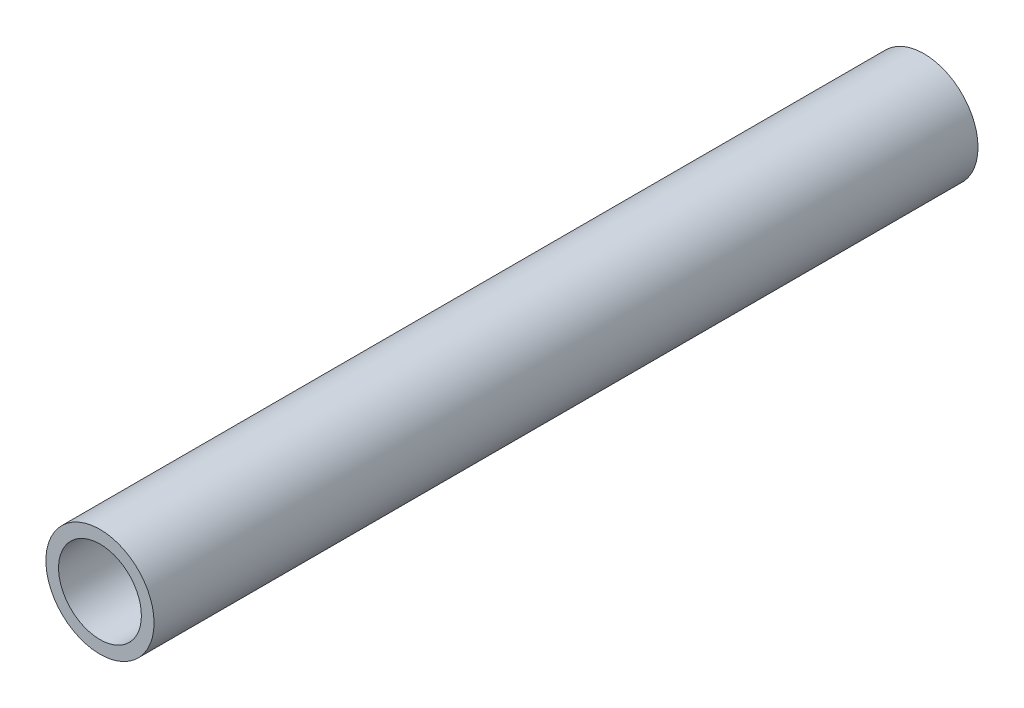
SolidWorks part; units mm, degrees
material "PVC Rigid"
ref_plane "Front Plane" through (0, 0, 0) normal (0, 0, 1) x (1, 0, 0)
ref_plane "Top Plane" through (0, 0, 0) normal (0, 1, 0) x (1, 0, 0)
ref_plane "Right Plane" through (0, 0, 0) normal (1, 0, 0) x (0, 0, -1)
sketch "Sketch1" plane through (0, 0, 0) normal (0, 0, 1) x (1, 0, 0)
  circle A0 centre (0, 0) radius 13.335
  circle A1 centre (0, 0) radius 10.2108
  dimension "D1" = 26.67
  dimension "D2" = 20.4216
extrude "Boss-Extrude1" add sketch "Sketch1" along normal mid plane 203.2
